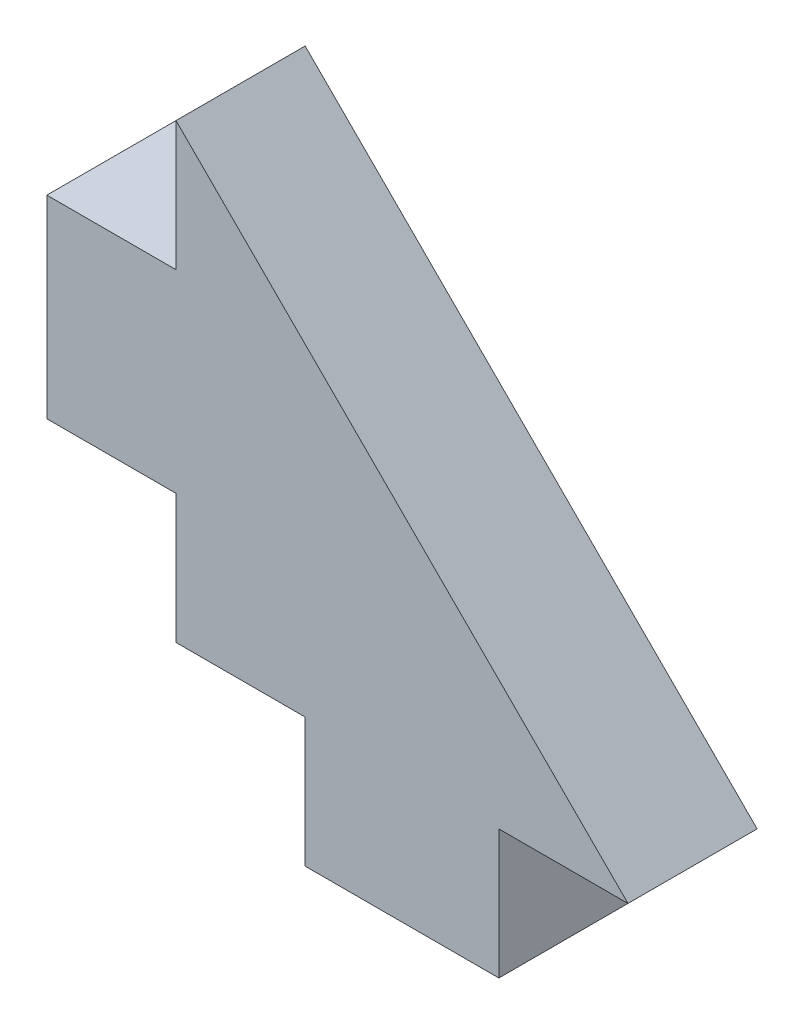
SolidWorks part; units mm, degrees
ref_plane "Front Plane" through (0, 0, 0) normal (0, 0, 1) x (1, 0, 0)
ref_plane "Top Plane" through (0, 0, 0) normal (0, 1, 0) x (1, 0, 0)
ref_plane "Right Plane" through (0, 0, 0) normal (1, 0, 0) x (0, 0, -1)
sketch "Sketch1" plane through (0, 0, 0) normal (0, 0, 1) x (1, 0, 0)
  line L0 (0, 0) -> (5.08, 0)
  line L2 (0, 17.78) -> (0, 12.7)
  line L3 (0, 17.78) -> (17.78, 0)
  line L4 (0, 0) -> (5.08, 0) construction
  line L6 (12.7, 0) -> (17.78, 0) construction
  line L7 (0, 0) -> (0, 5.08) construction
  line L8 (12.7, 0) -> (17.78, 0)
  line L9 (0, 12.7) -> (0, 17.78) construction
  line L10 (5.08, 0) -> (5.08, -5.08)
  line L11 (5.08, -5.08) -> (12.7, -5.08)
  line L12 (12.7, -5.08) -> (12.7, 0)
  line L13 (0, 5.08) -> (-5.08, 5.08)
  line L14 (-5.08, 5.08) -> (-5.08, 12.7)
  line L15 (-5.08, 12.7) -> (0, 12.7)
  line L16 (0, 5.08) -> (0, 0)
  dimension "D1" = 17.78
  dimension "D2" = 17.78
  dimension "D3" = 5.08
  dimension "D4" = 7.62
  dimension "D5" = 5.08
  dimension "D6" = 7.62
  dimension "D7" = 5.08
  dimension "D8" = 5.08
extrude "Boss-Extrude1" add sketch "Sketch1" along normal blind 5.08
equation "\"FoamCore\" = \".2\""
equation "\"MDF\" = \".2\""
equation "\"GMaterial\"= \".2\""
equation "\"PVCMountDiameter\" = \"0.5in\""
equation "\"PVCMountDistanceToEdge\" = \"0.5\""
equation "\"PVCThickness\" = \"0.13in\""
equation "\"PVCDiameter\" = 1.5in"
equation "\"BaseWidth\" = \"8in\""
equation "\"BaseLength\" = \"10in\""
equation "\"BallDiameter\" = \"38mm\""
equation "\"BaseGap\" = \"4in\""
equation "\"FunnelTopDiameter\" = \"8in\""
equation "\"FunnelTopDepth\" = \"0.5in\""
equation "\"BallGap\" = \"0.1in\""
equation "\"FunnelLength\" = 3in"
equation "\"FunnelMaterial\" = 0.1in"
equation "\"FunnelLowerDiameter\" = 1.9in"
equation "\"FunnelDepth\" = 1.5in"
equation "\"FunnelBendLength\" = 2*pi*\"FunnelLowerDiameter\"/2*135"
equation "\"AmmoFeederLength\" = 1.5in + 76mm"
equation "\"AmmoFeederCutoffLength\"= \"MovingWheelDiameter\""
equation "\"WheelThickness\" = 0.5in"
equation "\"LauncherWheelDiameter\" = 76mm"
equation "\"MotorFrontLength\" = 0.95in"
equation "\"MotorBodyTotalLength\" = 2.03in"
equation "\"MotorFrontDiameter\" = 1.5in"
equation "\"MotorLowerDriveshaftDiameter\" = 0.46in"
equation "\"MotorLowerDriveshaftThickness\" = 0.25in"
equation "\"MotorFullDriveshaftLength\" = 0.78in"
equation "\"MotorDriveshaftDiameter\" = 0.23in"
equation "\"MotorDriveshaftFlatThickness\" = 0.2in"
equation "\"MotorRearDiameter\" = 31.9mm"
equation "\"MotorDriveshaftBottomToTop\" = 31.1mm"
equation "\"MotorFlatDriveshaftLength\" = 11.7mm"
equation "\"MotorDistanceBetweenLowerandTopHoles\" = 0.5in"
equation "\"MotorMountsDistanceFromEdge\" = 0.06in"
equation "\"MotorScrewMountDiameter\" = 0.1in"
equation "\"MotorScrewMountDepth\" = 0.13in"
equation "\"HBRidgeScrewHoleDeep\" = 0.18in"
equation "\"MotorMountWidth\" = \"1.61in\""
equation "\"MotorMountLength\" = \"1.58in\""
equation "\"MotorMountToEdgeGap\" = \"3.3mm\""
equation "\"MotorMountToInsideEdgeGap\" = \"6.5mm\""
equation "\"MotorMountToMountWidthGap\" = \"25.8mm\""
equation "\"MotorMountToMountLengthGap\" = \"20.5mm\""
equation "\"MotorMountMaterialThickness\" = 1.6mm"
equation "\"MotorMountBaseScrewholeDiameter\" = 3.8mm"
equation "\"MotorMountBaseDistancebetweenHoles\" = 0.8in"
equation "\"MotorMountHeight\" = 1.85in"
equation "\"HBridgeWidth\" = 2.25in"
equation "\"HBridgeLength\" = 1.40in"
equation "\"UnoWidth\" = 3.13in"
equation "\"UnoLength\" = 3.06in"
equation "\"BatteryWidth\" = 1.15in"
equation "\"BatteryLength\" = 3.86in"
equation "\"ScrewDiameter\" = 2.7mm"
equation "\"MotorMountFaceScrewtoBase\" = 0.46in"
equation "\"MotorMountFaceDistanceBetweenScrews\" = 0.95in"
equation "\"MotorMountFaceMiddletoEdge\" = 0.16in"
equation "\"MotorMountFaceBottomtoEdge\" = 0.42in"
equation "\"MotorMountCenterholeHeight\" = 1.04in"
equation "\"MotorMountCenterholetoEdge\" = 0.25in"
equation "\"MovingWheelDiameter\" = 76mm"
equation "\"MovingWheelThickness\" = 0.5in"
equation "\"BraceLength\" = 1in"
equation "\"BraceVerticalOffset\" = 3.5in"
equation "\"BraceHorizontalOffset\" = 2.5in"
equation "\"BaseToBaseDistance\" = 3in"
equation "\"PVCOutsideDiameter\" = \"PVCDiameter\" + 2*\"PVCThickness\""
equation "\"Distancebetweenwalls\" = 6in"
equation "\"Slidewidth\" = 0.3in"
equation "\"Slidelength\" = 0.8in"
equation "\"Bottomtofloor\" = 0.53in"
equation "\"tabdistance\" = 0.2in"
equation "\"tabwidth\" = 0.3in"
equation "\"D3@Sketch1\"=\"tabdistance\""
equation "\"D4@Sketch1\"=\"tabwidth\""
equation "\"D5@Sketch1\"=\"tabdistance\""
equation "\"D6@Sketch1\"=\"tabwidth\""
equation "\"D7@Sketch1\"=\"MDF\""
equation "\"D8@Sketch1\"=\"MDF\""
